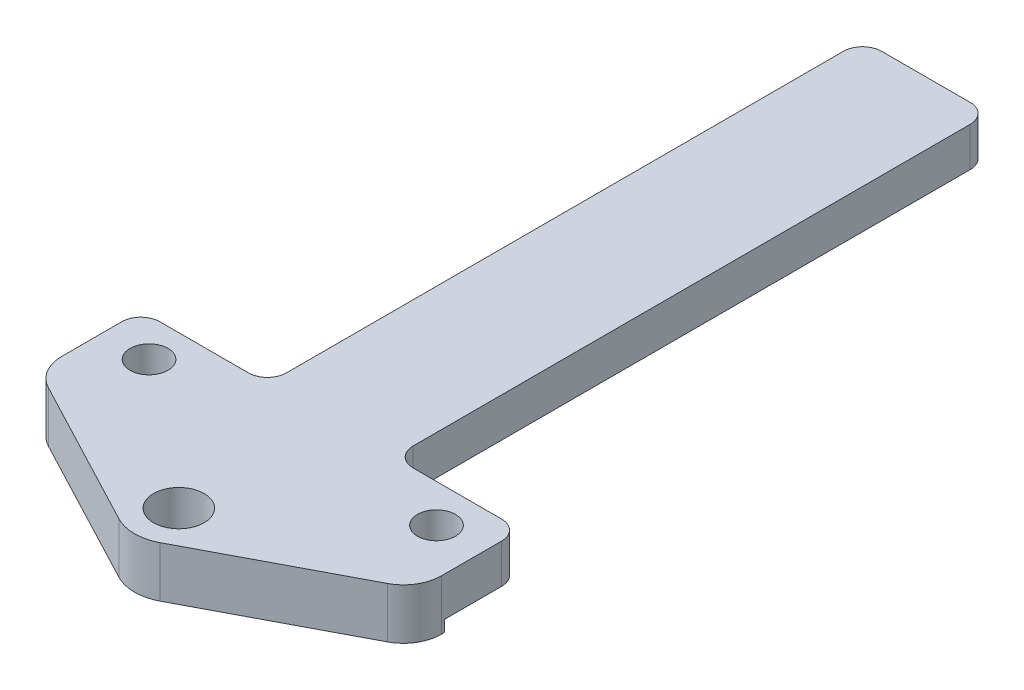
SolidWorks part; units mm, degrees
ref_plane "Plano frontal" through (0, 0, 0) normal (0, 0, 1) x (1, 0, 0)
ref_plane "Plano superior" through (0, 0, 0) normal (0, 1, 0) x (1, 0, 0)
ref_plane "Plano direito" through (0, 0, 0) normal (1, 0, 0) x (0, 0, -1)
sketch "Esboço1" plane through (0, 0, 0) normal (0, 1, 0) x (1, 0, 0)
  line L2 (0, -55) -> (0, 55) construction
  line L5 (-13.5, 12) -> (-5, 12)
  line L6 (0, 0) -> (0, 59) construction
  line L7 (5, 12) -> (13.5, 12)
  line L8 (-5, 59) -> (5, 59)
  line L10 (-5, 59) -> (-5, 12)
  line L13 (5, 59) -> (5, 12)
  line L14 (-5, 59) -> (5, 12) construction
  line L15 (-5, 12) -> (5, 59) construction
  line L16 (-15, 10.5) -> (-15, 5.7461)
  line L18 (-1.6292, -3.0977) -> (-13.3964, 3.0909)
  line L19 (1.6292, -3.0977) -> (13.3964, 3.0909)
  line L20 (15, 10.5) -> (15, 5.7461)
  circle A1 centre (0, 0) radius 2
  circle A2 centre (-11.35, 9) radius 1.5
  circle A3 centre (11.35, 9) radius 1.5
  arc A8 (15, 10.5) -> (13.5, 12) centre (13.5, 10.5) ccw
  arc A9 (-13.5, 12) -> (-15, 10.5) centre (-13.5, 10.5) ccw
  arc A11 (-1.6292, -3.0977) -> (1.6292, -3.0977) centre (0, 0) ccw
  arc A12 (15, 5.7461) -> (13.3964, 3.0909) centre (12, 5.7461) cw
  arc A13 (-13.3964, 3.0909) -> (-15, 5.7461) centre (-12, 5.7461) cw
  point P7 (0, 0)
  point P8 (0, 0)
  point P9 (-0.0212, 2)
  point P21 (15, 12)
  point P24 (-15, 12)
  point P25 (0, 35.5)
  point P28 (0, 0)
  point P32 (0, 0)
  dimension "D1" = 4
  dimension "D2" = 12
  dimension "D9" = 9
  dimension "D7" = 117.741
  dimension "D6" = 3
  dimension "D8" = 11.35
  dimension "D11" = 1.5
  dimension "D4" = 7
  dimension "D5" = 3
  dimension "D3" = 15
  dimension "D10" = 117.741
  dimension "D12" = 10
  dimension "D13" = 47
  dimension "D14" = 6.2539
extrude "Ressalto-extrusão1" add sketch "Esboço1" along normal mid plane 4
sketch "Esboço4" plane through (-5, 0, 0) normal (-1, 0, 0) x (0, 0, 1)
  line L1 (-59, -2) -> (-6, -2)
  line L2 (-59, -2) -> (-59, -1.1)
  line L3 (-59, -1.1) -> (-6, -1.1)
  line L4 (-6, -2) -> (-6, -1.1)
  dimension "D1" = 0.9
  dimension "D2" = 53
extrude "Corte-extrusão4" cut sketch "Esboço4" along normal up to next and the other way up to next
fillet "Filete2" radius 1.5 4 edges at (5, 0.45, -59) (-5, 0.45, -59) (5, 0.45, -12) (-5, 0.45, -12)
